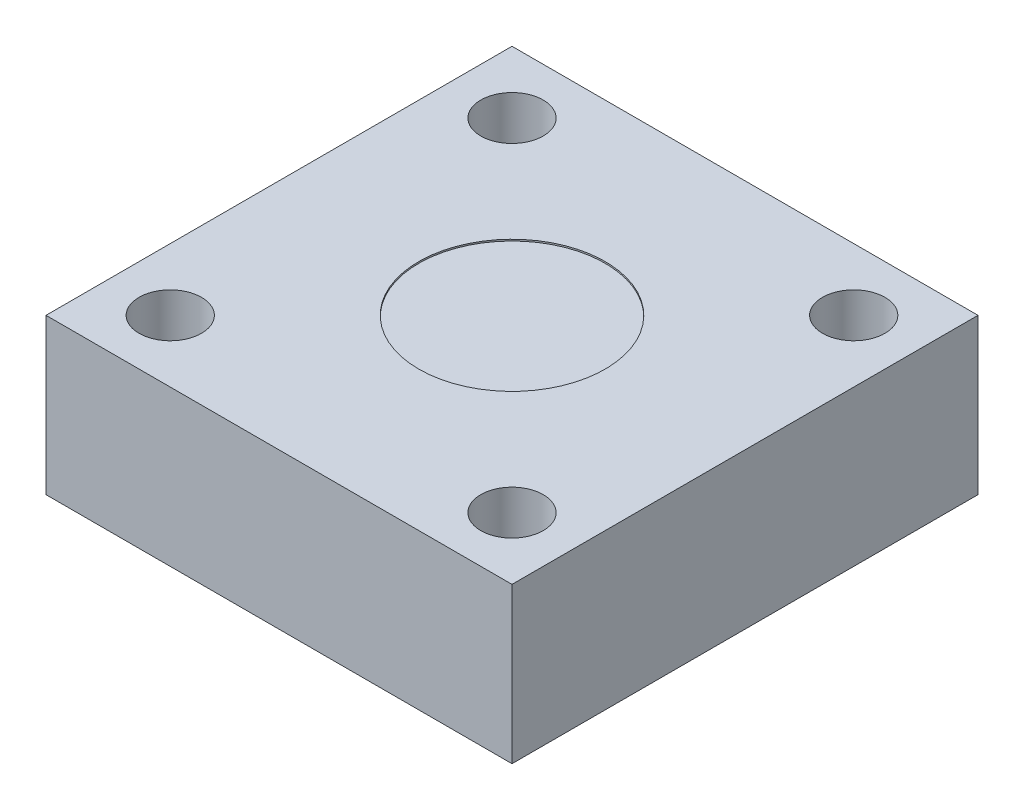
SolidWorks part; units mm, degrees
ref_plane "Front Plane" through (0, 0, 0) normal (0, 0, 1) x (1, 0, 0)
ref_plane "Top Plane" through (0, 0, 0) normal (0, 1, 0) x (1, 0, 0)
ref_plane "Right Plane" through (0, 0, 0) normal (1, 0, 0) x (0, 0, -1)
sketch "Sketch1" plane through (0, 0, 0) normal (0, 1, 0) x (1, 0, 0)
  line L1 (-19.05, 19.05) -> (19.05, 19.05)
  line L2 (-19.05, 19.05) -> (-19.05, -19.05)
  line L3 (-19.05, -19.05) -> (19.05, -19.05)
  line L4 (19.05, 19.05) -> (19.05, -19.05)
  line L5 (-19.05, 19.05) -> (19.05, -19.05) construction
  line L6 (-19.05, -19.05) -> (19.05, 19.05) construction
  point P0 (0, 0)
  dimension "D1" = 38.1
  dimension "D2" = 38.1
extrude "Boss-Extrude1" add sketch "Sketch1" along normal blind 12.7
sketch "Sketch2" plane through (0, 12.7, 0) normal (0, 1, 0) x (1, 0, 0)
  circle A0 centre (0, 0) radius 7.62
  dimension "D1" = 15.24
extrude "Cut-Extrude1" cut sketch "Sketch2" against normal blind 0.127
hole_wizard "Tap Drill for 1/4-20 Tap2" positions "Sketch7" profile "Sketch6" hole size "1/4-20" standard "ANSI Inch"
sketch "Sketch7" plane through (0, 12.7, 0) normal (0, 1, 0) x (1, 0, 0)
  line L0 (-19.05, 19.05) -> (-19.05, -19.05) construction
  line L1 (19.05, 19.05) -> (-19.05, 19.05) construction
  line L2 (19.05, -19.05) -> (19.05, 19.05) construction
  line L3 (-19.05, -19.05) -> (19.05, -19.05) construction
  point P0 (-13.97, 13.97)
  point P2 (13.97, 13.97)
  point P4 (13.97, -13.97)
  point P6 (-13.97, -13.97)
  dimension "D1" = 5.08
  dimension "D2" = 5.08
  dimension "D3" = 5.08
  dimension "D4" = 5.08
  dimension "D5" = 5.08
  dimension "D6" = 5.08
  dimension "D7" = 5.08
  dimension "D8" = 5.08
sketch "Sketch6" plane through (-13.97, 12.7, -13.97) normal (1, 0, 0) x (0, 0, 1)
  line L0 (0, 0) -> (0, 7.8838)
  line L1 (0, 7.8838) -> (2.5527, 6.35)
  line L2 (2.5527, 6.35) -> (2.5527, 0)
  line L5 (2.5527, 0) -> (0, 0)
  line L10 (0, 7.8838) -> (-2.5527, 6.35) construction
  line L11 (0, -6.35) -> (0, 107.95) construction
  dimension "Hole Dia." = 5.1054
  dimension "Hole Depth" = 6.35
  dimension "Drill Angle" = 118
